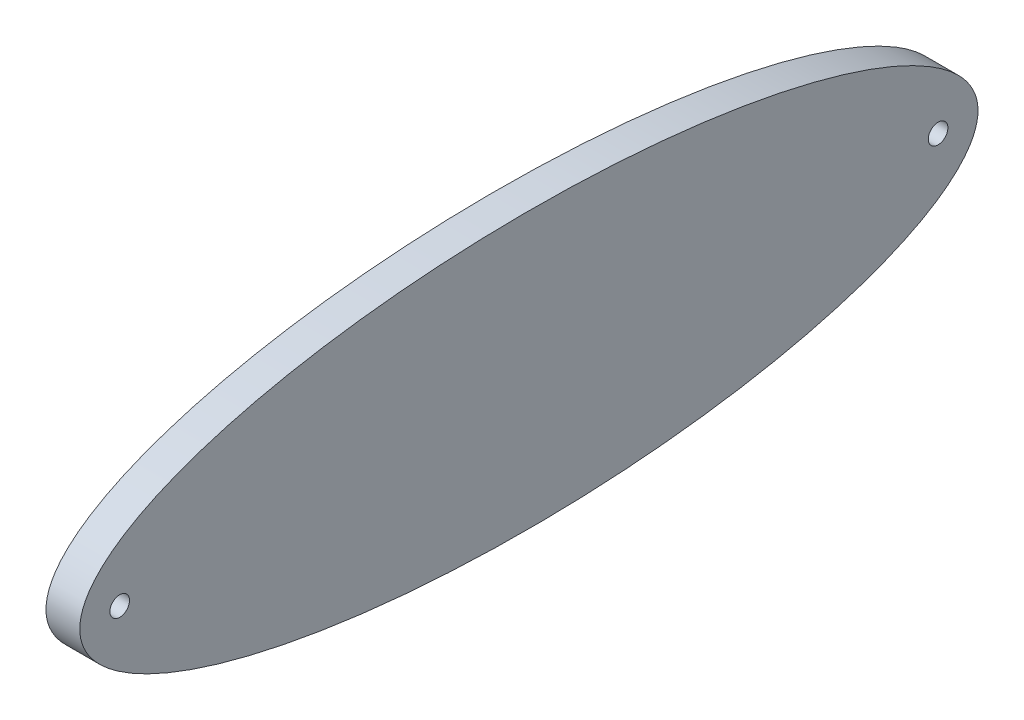
SolidWorks part; units mm, degrees
ref_plane "Front Plane" through (0, 0, 0) normal (0, 0, 1) x (1, 0, 0)
ref_plane "Top Plane" through (0, 0, 0) normal (0, 1, 0) x (1, 0, 0)
ref_plane "Right Plane" through (0, 0, 0) normal (1, 0, 0) x (0, 0, -1)
sketch "Sketch1" plane through (0, 0, 0) normal (1, 0, 0) x (0, 0, -1)
  circle A0 centre (-61.5, 0) radius 1.4732
  circle A1 centre (61.5, 0) radius 1.4732
  ellipse E0 centre (0, 0) end of major axis (67.5, 0) minor radius 20.7
  dimension "D3" = 2.9464
  dimension "D4" = 2.9464
  dimension "D1" = 41.4
  dimension "D2" = 135
  dimension "D5" = 6
  dimension "D6" = 6
extrude "Boss-Extrude1" add sketch "Sketch1" along normal blind 5.08
